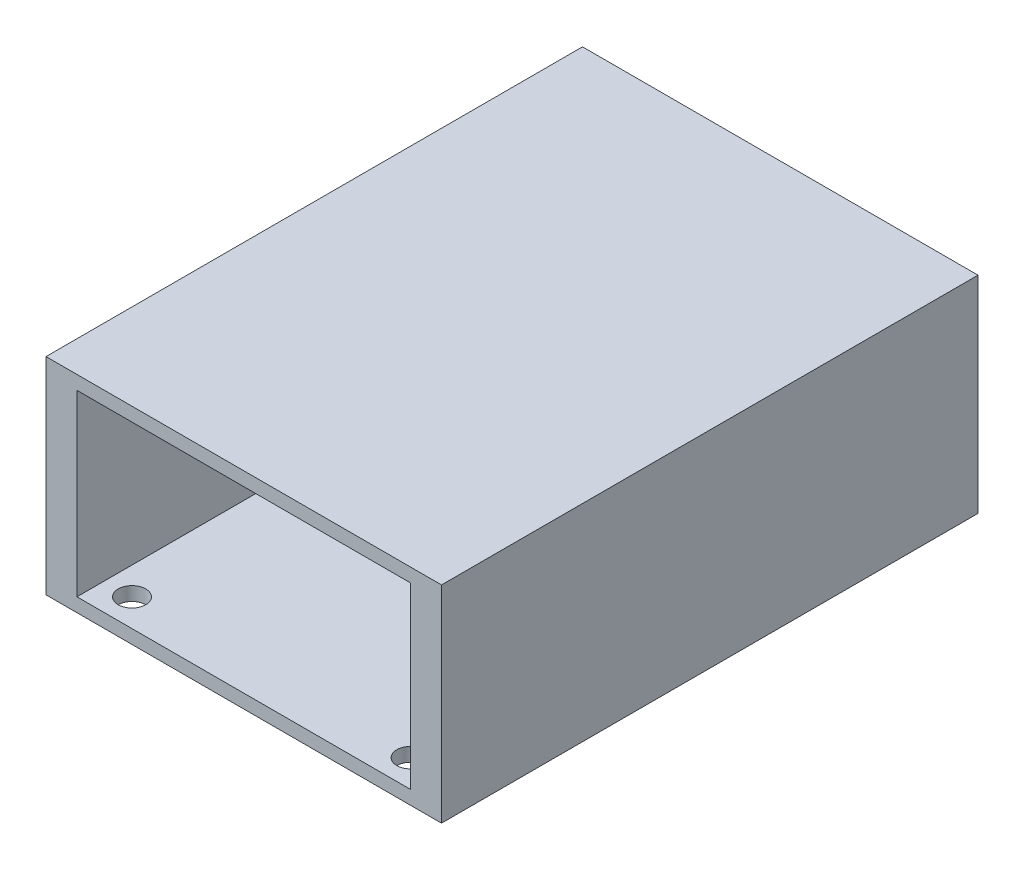
SolidWorks part; units mm, degrees
ref_plane "Front Plane" through (0, 0, 0) normal (0, 0, 1) x (1, 0, 0)
ref_plane "Top Plane" through (0, 0, 0) normal (0, 1, 0) x (1, 0, 0)
ref_plane "Right Plane" through (0, 0, 0) normal (1, 0, 0) x (0, 0, -1)
sketch "Sketch1" plane through (0, 0, 0) normal (0, 1, 0) x (1, 0, 0)
  line L1 (-33.598, 40.2304) -> (23.902, 40.2304)
  line L2 (-33.598, 40.2304) -> (-33.598, -37.7696)
  line L3 (-33.598, -37.7696) -> (23.902, -37.7696)
  line L4 (23.902, 40.2304) -> (23.902, -37.7696)
  dimension "D1" = 57.5
  dimension "D2" = 78
extrude "Boss-Extrude1" add sketch "Sketch1" along normal blind 30
sketch "Sketch2" plane through (0, 0, 37.7696) normal (0, 0, 1) x (1, 0, 0)
  line L0 (23.902, 30) -> (23.902, 0) construction
  line L1 (-29.098, 28) -> (19.402, 28)
  line L2 (-29.098, 28) -> (-29.098, 2)
  line L3 (-29.098, 2) -> (19.402, 2)
  line L4 (19.402, 28) -> (19.402, 2)
  line L7 (-33.598, 0) -> (23.902, 0) construction
  line L8 (-33.598, 30) -> (23.902, 30) construction
  dimension "D1" = 48.5
  dimension "D2" = 4.5
  dimension "D3" = 2
  dimension "D4" = 2
extrude "Cut-Extrude1" cut sketch "Sketch2" against normal blind 76
sketch "Sketch3" plane through (0, 2, 0) normal (0, 1, 0) x (1, 0, 0)
  line L0 (-29.098, -37.7696) -> (19.402, -37.7696) construction
  line L1 (19.402, 38.2304) -> (19.402, -37.7696) construction
  line L2 (-29.098, 38.2304) -> (19.402, 38.2304) construction
  line L3 (-29.098, 38.2304) -> (-29.098, -37.7696) construction
  circle A0 centre (15.402, -33.7696) radius 2
  circle A1 centre (-25.098, 34.2304) radius 1
  circle A2 centre (-25.098, -33.7696) radius 2
  dimension "D1" = 4
  dimension "D3" = 4
  dimension "D5" = 4
  dimension "D2" = 4
  dimension "D4" = 4
  dimension "D6" = 4
extrude "Cut-Extrude2" cut sketch "Sketch3" against normal through all
